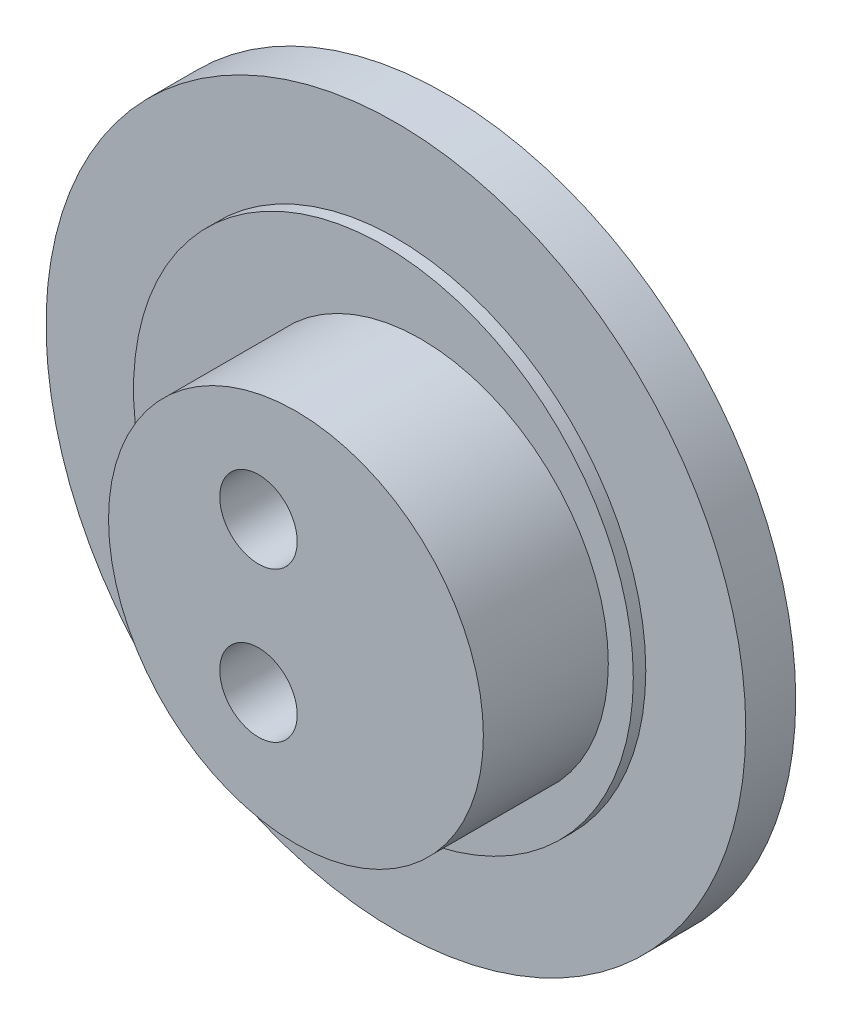
SolidWorks part; units mm, degrees
ref_plane "Front Plane" through (0, 0, 0) normal (0, 0, 1) x (1, 0, 0)
ref_plane "Top Plane" through (0, 0, 0) normal (0, 1, 0) x (1, 0, 0)
ref_plane "Right Plane" through (0, 0, 0) normal (1, 0, 0) x (0, 0, -1)
sketch "Sketch1" plane through (0, 0, 0) normal (0, 0, 1) x (1, 0, 0)
  circle A0 centre (0, 0) radius 10
  dimension "D1" = 20
extrude "Boss-Extrude1" add sketch "Sketch1" along normal blind 0.5
sketch "Sketch4" plane through (0, 0, 0.5) normal (0, 0, 1) x (1, 0, 0)
  circle A0 centre (0, 0) radius 14
  dimension "D1" = 28
extrude "Boss-Extrude3" add sketch "Sketch4" along normal blind 2
sketch "Sketch5" plane through (0, 0, 2.5) normal (0, 0, 1) x (1, 0, 0)
  circle A0 centre (0, 0) radius 10
  dimension "D1" = 20
extrude "Boss-Extrude4" add sketch "Sketch5" along normal blind 0.5
sketch "Sketch6" plane through (0, 0, 3) normal (0, 0, 1) x (1, 0, 0)
  line L0 (0, 0) -> (15.7428, 0) construction
  circle A0 centre (1.5, 0) radius 7.5
  point P3 (1.5, 0)
  dimension "D2" = 15
  dimension "D1" = 1.5
extrude "Boss-Extrude6" add sketch "Sketch6" along normal blind 5
sketch "Sketch7" plane through (0, 0, 8) normal (0, 0, 1) x (1, 0, 0)
  line L0 (0, 0) -> (0, 14.4991) construction
  line L1 (-6.9386, 0) -> (18.3284, 0) construction
  circle A0 centre (0, 3) radius 1.55
  circle A1 centre (0, -3) radius 1.55
  dimension "D1" = 3.1
  dimension "D2" = 3
extrude "Cut-Extrude1" cut sketch "Sketch7" against normal through all
